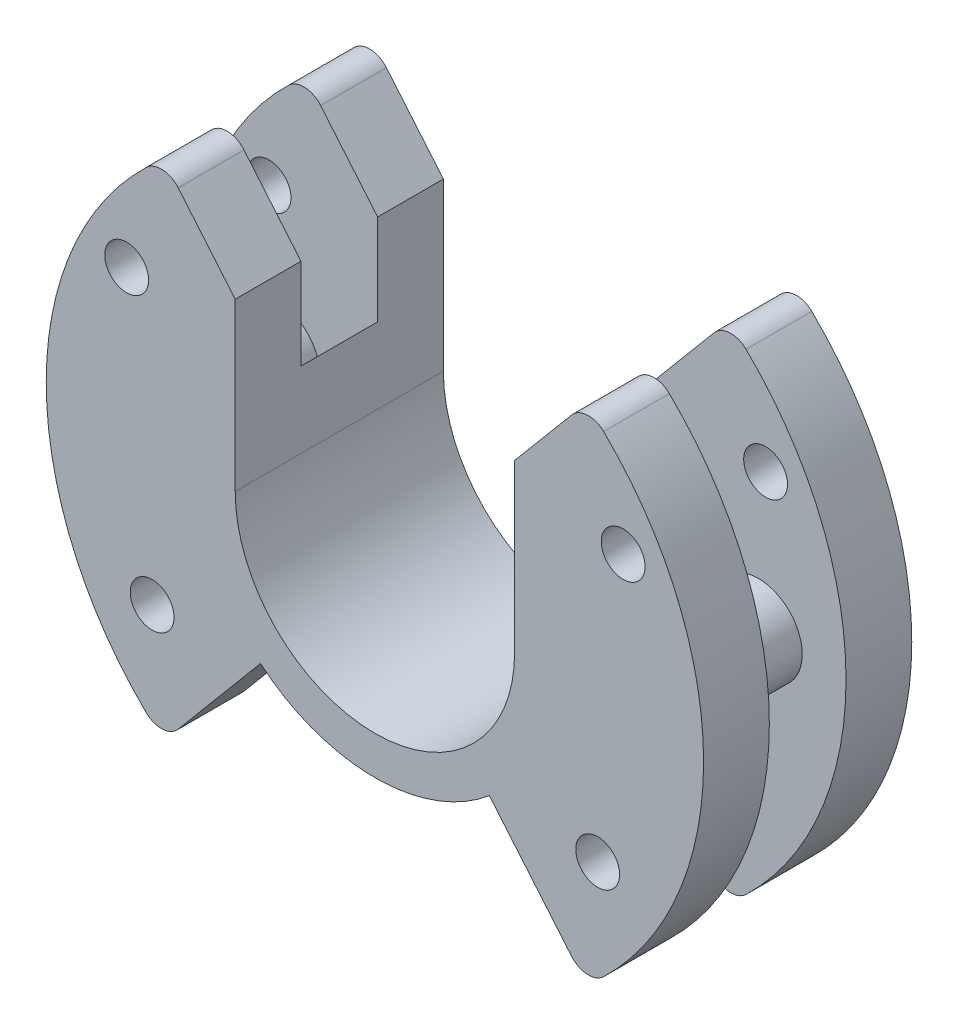
SolidWorks part; units mm, degrees
ref_plane "Front Plane" through (0, 0, 0) normal (0, 0, 1) x (1, 0, 0)
ref_plane "Top Plane" through (0, 0, 0) normal (0, 1, 0) x (1, 0, 0)
ref_plane "Right Plane" through (0, 0, 0) normal (1, 0, 0) x (0, 0, -1)
sketch "Sketch1" plane through (0, 0, 0) normal (0, 0, 1) x (1, 0, 0)
  circle A0 centre (0, 0) radius 30
  dimension "D1" = 60
extrude "Boss-Extrude1" add sketch "Sketch1" against normal blind 6
sketch "Sketch2" plane through (0, 0, 0) normal (0, 0, 1) x (1, 0, 0)
  circle A0 centre (0, 0) radius 14.5
  dimension "D1" = 29
extrude "Boss-Extrude2" add sketch "Sketch2" along normal blind 13
sketch "Sketch3" plane through (0, 0, 13) normal (0, 0, 1) x (1, 0, 0)
  circle A0 centre (0, 0) radius 12.75
  dimension "D1" = 25.5
extrude "Cut-Extrude1" cut sketch "Sketch3" against normal through all both and the other way through all
sketch "Sketch5" plane through (0, 0, 0) normal (0, 0, 1) x (1, 0, 0)
  circle A0 centre (0, 0) radius 30
  circle A1 centre (0, 0) radius 12.75
  circle A2 centre (0, 0) radius 12.75 construction
  circle A3 centre (0, 0) radius 30 construction
extrude "Boss-Extrude4" add sketch "Sketch5" against normal blind 6 from surface at 13 starting at face at (12.75, 0, 13)
sketch "Sketch6" plane through (0, 0, 0) normal (0, 0, 1) x (1, 0, 0)
  line L0 (-30, 0) -> (0, 0) construction
  line L1 (0, -41.069) -> (0, 41.069) construction
  line L2 (-40.6561, -12.75) -> (0, -12.75) construction
  line L3 (-20.3332, 0) -> (-20.3332, -41.5595) construction
  line L4 (-22.6592, 0) -> (-22.6592, 41.4208) construction
  line L6 (-40.6561, 12.75) -> (0, 12.75) construction
  circle A0 centre (0, 0) radius 12.75 construction
  circle A1 centre (-20.3332, -12.75) radius 2
  circle A2 centre (0, 0) radius 30 construction
  circle A4 centre (-22.6592, 12.75) radius 2
  circle A7 centre (20.3332, -12.75) radius 2
  circle A10 centre (22.6592, 12.75) radius 2
  dimension "D1" = 4
  dimension "D2" = 24
  dimension "D5" = 4
  dimension "D4" = 26
extrude "Cut-Extrude2" cut sketch "Sketch6" against normal through all both and the other way through all
sketch "Sketch7" plane through (0, 0, 13) normal (0, 0, 1) x (1, 0, 0)
  line L0 (0, 0) -> (-12.75, 0) construction
  line L1 (0, 0) -> (0, 12.75) construction
  line L2 (0, 0) -> (-27.5333, -32.8129) construction
  line L3 (0, 0) -> (27.5333, -32.8129) construction
  line L4 (10.4453, -12.4482) -> (19.2836, -22.9813)
  line L5 (-10.4453, 12.4482) -> (-19.2836, 22.9813)
  line L6 (-10.4453, -12.4482) -> (-19.2836, -22.9813)
  line L7 (10.4453, 12.4482) -> (19.2836, 22.9813)
  arc A0 (-10.4453, 12.4482) -> (10.4453, 12.4482) centre (0, 0) cw
  arc A1 (-19.2836, 22.9813) -> (19.2836, 22.9813) centre (0, 0) cw
  circle A4 centre (0, 0) radius 12.75 construction
  circle A5 centre (0, 0) radius 30 construction
  arc A6 (-10.4453, -12.4482) -> (10.4453, -12.4482) centre (0, 0) ccw
  arc A7 (-19.2836, -22.9813) -> (19.2836, -22.9813) centre (0, 0) ccw
  dimension "D2" = 3.5
  dimension "D1" = 50
  dimension "D3" = 50
extrude "Cut-Extrude3" cut sketch "Sketch7" against normal through all both and the other way through all
fillet "Fillet1" radius 2 1 edges at (-19.2836, -22.9813, 10)
fillet "Fillet2" radius 2 1 edges at (-19.2836, 22.9813, 10)
fillet "Fillet3" radius 2 1 edges at (19.2836, 22.9813, 10)
fillet "Fillet4" radius 2 1 edges at (19.2836, -22.9813, 10)
sketch "Sketch8" plane through (0, 0, 13) normal (0, 0, 1) x (1, 0, 0)
  line L0 (0, 42.8702) -> (0, -42.8702) construction
  line L1 (-42.07, 0) -> (42.07, 0) construction
  circle A9 centre (-22, 0) radius 4
  circle A11 centre (22, 0) radius 4
  dimension "D6" = 8
  dimension "D7" = 22
extrude "Boss-Extrude5" add sketch "Sketch8" against normal up to surface (13 mm away) up to face at (0, 0, 0)
fillet "Fillet5" radius 2 1 edges at (-19.2836, 22.9813, -3)
fillet "Fillet6" radius 2 1 edges at (-19.2836, -22.9813, -3)
fillet "Fillet7" radius 2 1 edges at (19.2836, -22.9813, -3)
fillet "Fillet8" radius 2 1 edges at (19.2836, 22.9813, -3)
sketch "Sketch10" plane through (0, 0, 13) normal (0, 0, 1) x (1, 0, 0)
  line L0 (0, 23.4531) -> (0, -27.6078) construction
  line L1 (-33.7286, -30) -> (35, -30) construction
  line L2 (-33.7286, 12.75) -> (35, 12.75) construction
  arc A1 (-20.8759, 21.5452) -> (-20.8759, -21.5452) centre (0, 0) ccw construction
sketch "Sketch11" plane through (0, 0, -6) normal (0, 0, -1) x (-1, 0, 0)
  line L4 (-12.75, 0) -> (-12.75, 25)
  line L5 (12.75, 0) -> (12.75, 25)
  line L6 (12.75, 25) -> (-12.75, 25)
  line L7 (-12.75, 0) -> (12.75, 0)
  circle A0 centre (0, 0) radius 12.75 construction
  dimension "D1" = 25
extrude "Cut-Extrude4" cut sketch "Sketch11" against normal through all both and the other way through all
